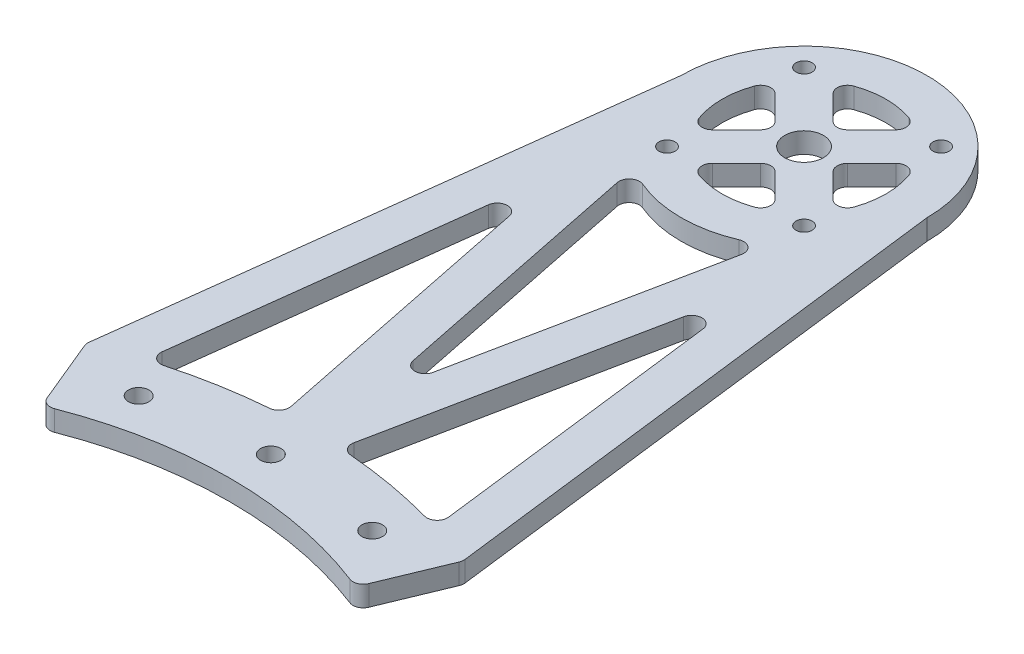
SolidWorks part; units mm, degrees
material "Acrylic (Medium-high impact)"
ref_plane "Front Plane" through (0, 0, 0) normal (0, 0, 1) x (1, 0, 0)
ref_plane "Top Plane" through (0, 0, 0) normal (0, 1, 0) x (1, 0, 0)
ref_plane "Right Plane" through (0, 0, 0) normal (1, 0, 0) x (0, 0, -1)
sketch "Sketch1" plane through (0, 0, 0) normal (0, 1, 0) x (1, 0, 0)
  line L0 (-19.0617, 152.3052) -> (-29.1093, 70.8149)
  line L2 (19.0617, 152.3052) -> (29.1093, 70.8149)
  line L4 (-13.4978, 120.2663) -> (-4.8654, 77.8385)
  line L6 (-9.6268, 133.0897) -> (-1.5556, 93.4205)
  line L7 (-24.9005, 60.1151) -> (-29.0004, 70.0131)
  line L8 (1.5556, 93.4205) -> (9.6268, 133.0897)
  line L9 (24.9005, 60.1151) -> (29.0004, 70.0131)
  line L14 (4.8545, 161.7446) -> (1.1225, 158.0127)
  line L16 (-1.1225, 146.7873) -> (-4.8545, 143.0554)
  line L17 (9.3446, 157.2545) -> (5.6127, 153.5225)
  line L24 (4.8654, 77.8385) -> (13.4978, 120.2663)
  line L28 (16.629, 120.144) -> (22.1698, 75.2061)
  line L31 (-1.1225, 158.0127) -> (-4.8545, 161.7446)
  line L33 (-5.6127, 153.5225) -> (-9.3446, 157.2545)
  line L35 (-5.6127, 151.2775) -> (-9.3446, 147.5455)
  line L36 (-16.629, 120.144) -> (-22.1698, 75.2061)
  line L37 (4.8545, 143.0554) -> (1.1225, 146.7873)
  line L38 (9.3446, 147.5455) -> (5.6127, 151.2775)
  arc A0 (19.0498, 152.4918) -> (-19.0498, 152.4918) centre (0, 152.4) ccw
  arc A1 (22.8623, 59.2416) -> (24.9005, 60.1151) centre (23.4338, 60.7226) ccw
  circle A2 centre (-10.6066, 163.0066) radius 1.25
  circle A3 centre (0, 69.85) radius 1.5875
  circle A4 centre (18.0785, 67.4699) radius 1.5875
  circle A5 centre (10.6066, 163.0066) radius 1.25
  circle A6 centre (10.6066, 141.7934) radius 1.25
  arc A7 (4.2651, 164.3624) -> (-4.2651, 164.3624) centre (0, 152.4) ccw
  arc A8 (-4.2651, 140.4376) -> (4.2651, 140.4376) centre (0, 152.4) ccw
  arc A9 (11.9624, 148.1349) -> (11.9624, 156.6651) centre (0, 152.4) ccw
  arc A10 (20.1739, 73.481) -> (6.29, 75.9399) centre (0, 0) ccw
  arc A11 (-11.9624, 156.6651) -> (-11.9624, 148.1349) centre (0, 152.4) ccw
  arc A12 (-6.29, 75.9399) -> (-20.1739, 73.481) centre (0, 0) ccw
  circle A13 centre (-10.6066, 141.7934) radius 1.25
  arc A14 (9.3446, 147.5455) -> (11.9624, 148.1349) centre (10.4671, 148.6681) ccw
  arc A15 (-4.8545, 143.0554) -> (-4.2651, 140.4376) centre (-3.7319, 141.9329) ccw
  arc A16 (-11.9624, 148.1349) -> (-9.3446, 147.5455) centre (-10.4671, 148.6681) ccw
  arc A17 (-5.6127, 153.5225) -> (-5.6127, 151.2775) centre (-6.7352, 152.4) cw
  arc A18 (-1.1225, 158.0127) -> (1.1225, 158.0127) centre (0, 159.1352) ccw
  arc A19 (1.1225, 146.7873) -> (-1.1225, 146.7873) centre (0, 145.6648) ccw
  arc A20 (5.6127, 151.2775) -> (5.6127, 153.5225) centre (6.7352, 152.4) cw
  arc A21 (4.8545, 143.0554) -> (4.2651, 140.4376) centre (3.7319, 141.9329) cw
  arc A22 (22.1698, 75.2061) -> (20.1739, 73.481) centre (20.5942, 75.0118) cw
  arc A23 (9.3446, 157.2545) -> (11.9624, 156.6651) centre (10.4671, 156.1319) cw
  arc A24 (4.8545, 161.7446) -> (4.2651, 164.3624) centre (3.7319, 162.8671) ccw
  arc A25 (-4.2651, 164.3624) -> (-4.8545, 161.7446) centre (-3.7319, 162.8671) ccw
  circle A26 centre (-18.0785, 67.4699) radius 1.5875
  arc A27 (-22.1698, 75.2061) -> (-20.1739, 73.481) centre (-20.5942, 75.0118) ccw
  arc A28 (4.8654, 77.8385) -> (6.29, 75.9399) centre (6.421, 77.522) ccw
  arc A29 (16.629, 120.144) -> (13.4978, 120.2663) centre (15.0534, 119.9498) ccw
  arc A30 (-16.629, 120.144) -> (-13.4978, 120.2663) centre (-15.0534, 119.9498) cw
  arc A31 (-7.4503, 134.8673) -> (7.4503, 134.8673) centre (0, 152.4) ccw
  arc A32 (-4.8654, 77.8385) -> (-6.29, 75.9399) centre (-6.421, 77.522) cw
  arc A33 (-9.6268, 133.0897) -> (-7.4503, 134.8673) centre (-8.0712, 133.4062) cw
  arc A34 (22.8623, 59.2416) -> (-22.8623, 59.2416) centre (0, 0) ccw
  circle A35 centre (49.3914, 49.3914) radius 1.5875 [skipped]
  circle A36 centre (60.4919, 34.925) radius 1.5875 [skipped]
  circle A37 centre (67.4699, 18.0785) radius 1.5875 [skipped]
  circle A38 centre (69.85, 0) radius 1.5875 [skipped]
  circle A39 centre (67.4699, -18.0785) radius 1.5875 [skipped]
  circle A40 centre (60.4919, -34.925) radius 1.5875 [skipped]
  circle A41 centre (49.3914, -49.3914) radius 1.5875 [skipped]
  circle A42 centre (34.925, -60.4919) radius 1.5875 [skipped]
  circle A43 centre (18.0785, -67.4699) radius 1.5875 [skipped]
  circle A44 centre (0, -69.85) radius 1.5875 [skipped]
  circle A45 centre (-18.0785, -67.4699) radius 1.5875 [skipped]
  circle A46 centre (-34.925, -60.4919) radius 1.5875 [skipped]
  circle A47 centre (-49.3914, -49.3914) radius 1.5875 [skipped]
  circle A48 centre (-60.4919, -34.925) radius 1.5875 [skipped]
  circle A49 centre (-67.4699, -18.0785) radius 1.5875 [skipped]
  circle A50 centre (-69.85, 0) radius 1.5875 [skipped]
  circle A51 centre (-67.4699, 18.0785) radius 1.5875 [skipped]
  circle A52 centre (-60.4919, 34.925) radius 1.5875 [skipped]
  circle A53 centre (-49.3914, 49.3914) radius 1.5875 [skipped]
  circle A54 centre (-34.925, 60.4919) radius 1.5875 [skipped]
  circle A55 centre (34.925, 60.4919) radius 1.5875 [skipped]
  circle A57 centre (0, 152.4) radius 3
  arc A58 (9.6268, 133.0897) -> (7.4503, 134.8673) centre (8.0712, 133.4062) ccw
  arc A59 (-1.5556, 93.4205) -> (1.5556, 93.4205) centre (0, 93.737) ccw
  arc A60 (-11.9624, 156.6651) -> (-9.3446, 157.2545) centre (-10.4671, 156.1319) cw
  arc A61 (19.0617, 152.3052) -> (19.0498, 152.4918) centre (20.6373, 152.4994) cw
  arc A62 (29.0004, 70.0131) -> (29.1093, 70.8149) centre (27.5337, 70.6206) ccw
  arc A63 (-29.1093, 70.8149) -> (-29.0004, 70.0131) centre (-27.5337, 70.6206) ccw
  arc A64 (-24.9005, 60.1151) -> (-22.8623, 59.2416) centre (-23.4338, 60.7226) ccw
  arc A65 (-19.0617, 152.3052) -> (-19.0498, 152.4918) centre (-20.6373, 152.4994) ccw
  point P30 (0, 152.4)
  point P31 (0, 152.4)
  point P34 (10.9402, 145.95)
  point P46 (-4.4901, 152.4)
  point P56 (0, 0)
  point P64 (0, 147.9099)
  point P71 (0, 0)
  point P134 (-4.5049, 76.0667)
  point P145 (19.05, 152.4)
  dimension "D1" = 4
  dimension "D2" = 1.5875
extrude "Boss-Extrude1" add sketch "Sketch1" along normal blind 3.175
